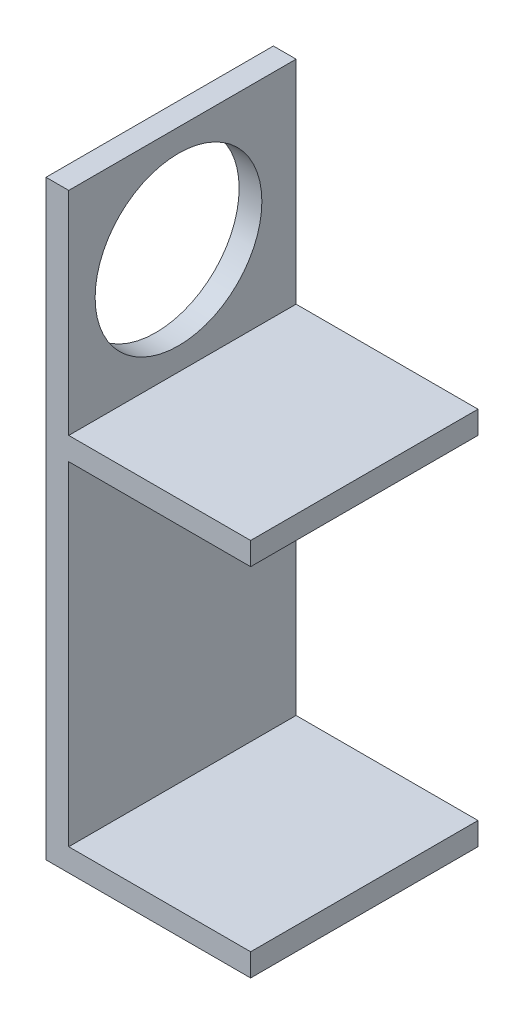
SolidWorks part; units mm, degrees
ref_plane "前视基准面" through (0, 0, 0) normal (0, 0, 1) x (1, 0, 0)
ref_plane "上视基准面" through (0, 0, 0) normal (0, 1, 0) x (1, 0, 0)
ref_plane "右视基准面" through (0, 0, 0) normal (1, 0, 0) x (0, 0, -1)
other "Configuration Table"
sketch "草图1" plane through (0, 0, 0) normal (0, 0, 1) x (1, 0, 0)
  line L0 (27, 47) -> (27, 50)
  line L1 (0, 0) -> (27, 0)
  line L2 (0, 0) -> (0, 50)
  line L3 (0, 50) -> (27, 50)
  line L4 (27, 0) -> (27, 3)
  line L5 (27, 47) -> (3, 47)
  line L7 (27, 3) -> (3, 3)
  line L8 (3, 47) -> (3, 3)
  dimension "D1" = 24
  dimension "D2" = 44
  dimension "D3" = 3
  dimension "D4" = 3
  dimension "D5" = 3
extrude "凸台-拉伸1" add sketch "草图1" along normal blind 30
sketch "草图2" plane through (0, 50, 0) normal (0, 1, 0) x (1, 0, 0)
  line L0 (0, -30) -> (0, 0) construction
  line L1 (0, -30) -> (3, -30)
  line L2 (0, -30) -> (0, 0)
  line L3 (0, 0) -> (3, 0)
  line L4 (3, -30) -> (3, 0)
  line L5 (27, 0) -> (0, 0) construction
  dimension "D1" = 3
extrude "凸台-拉伸2" add sketch "草图2" along normal blind 28
sketch "草图3" plane through (0, 0, 0) normal (-1, 0, 0) x (0, 0, 1)
  circle A0 centre (15.518, 64) radius 11
extrude "切除-拉伸1" cut sketch "草图3" against normal up to next
